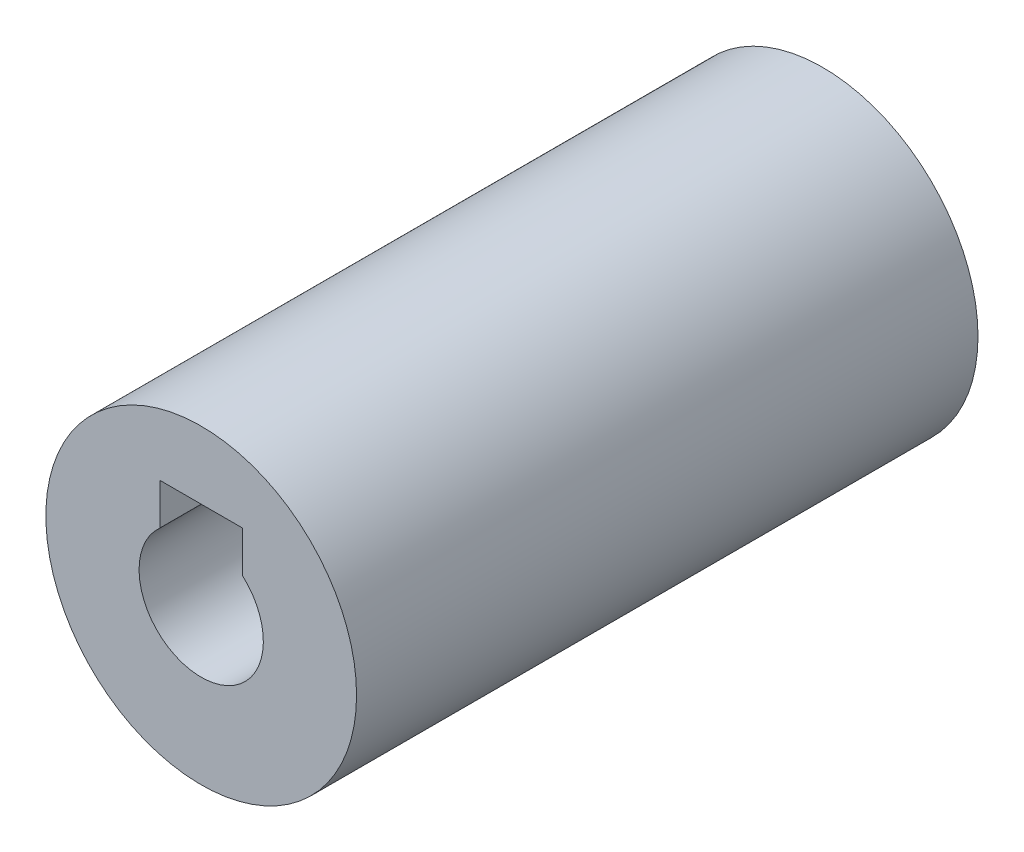
SolidWorks part; units mm, degrees
material "2024-T4"
ref_plane "Front Plane" through (0, 0, 0) normal (0, 0, 1) x (1, 0, 0)
ref_plane "Top Plane" through (0, 0, 0) normal (0, 1, 0) x (1, 0, 0)
ref_plane "Right Plane" through (0, 0, 0) normal (1, 0, 0) x (0, 0, -1)
sketch "Sketch1" plane through (0, 0, 0) normal (0, 0, 1) x (1, 0, 0)
  circle A0 centre (0, 0) radius 3
  circle A1 centre (0, 0) radius 7.5
  dimension "D1" = 15
  dimension "D2" = 6
extrude "Boss-Extrude1" add sketch "Sketch1" along normal blind 30
sketch "Sketch2" plane through (0, 0, 30) normal (0, 0, 1) x (1, 0, 0)
  line L0 (0, 0) -> (0, 6.5951) construction
  line L1 (2, 4.2361) -> (-2, 4.2361)
  line L2 (-2, 4.2361) -> (-2, 2.2361)
  line L3 (2, 4.2361) -> (2, 2.2361)
  circle A0 centre (0, 0) radius 3 construction
  circle A1 centre (0, 0) radius 3
  point P11 (0, 4.2361)
  circle M6 centre (0, 0) radius 3
  dimension "D1" = 4
  dimension "D2" = 2
extrude "Cut-Extrude1" cut sketch "Sketch2" against normal through all contours L0 L1 L2 M6 | L0 A1 L3 L1
